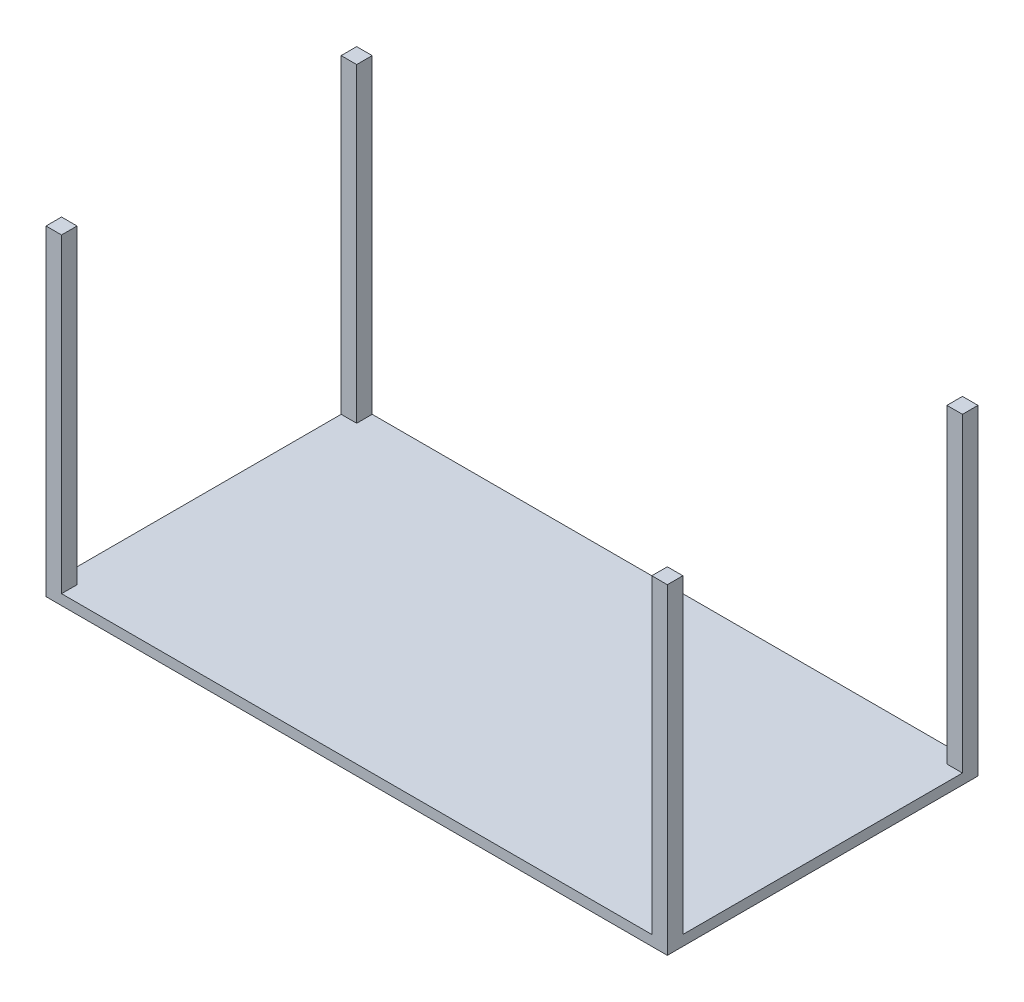
SolidWorks part; units mm, degrees
ref_plane "Front" through (0, 0, 0) normal (0, 0, 1) x (1, 0, 0)
ref_plane "Top" through (0, 0, 0) normal (0, 1, 0) x (1, 0, 0)
ref_plane "Right" through (0, 0, 0) normal (1, 0, 0) x (0, 0, -1)
sketch "Sketch1" plane through (0, 0, 0) normal (0, 1, 0) x (1, 0, 0)
  line L1 (-762, 381) -> (762, 381)
  line L2 (-762, 381) -> (-762, -381)
  line L3 (-762, -381) -> (762, -381)
  line L4 (762, 381) -> (762, -381)
  line L5 (-762, 381) -> (762, -381) construction
  line L6 (-762, -381) -> (762, 381) construction
  point P0 (0, 0)
  dimension "D1" = 1524
  dimension "D2" = 762
extrude "Boss-Extrude1" add sketch "Sketch1" along normal blind 25.4
sketch "Sketch2" plane through (0, 25.4, 0) normal (0, 1, 0) x (1, 0, 0)
  line L1 (-762, 381) -> (-723.9, 381)
  line L2 (-762, 381) -> (-762, 342.9)
  line L3 (-762, 342.9) -> (-723.9, 342.9)
  line L4 (-723.9, 381) -> (-723.9, 342.9)
  line L5 (-762, -381) -> (-723.9, -381)
  line L6 (-762, -381) -> (-762, -342.9)
  line L7 (-762, -342.9) -> (-723.9, -342.9)
  line L8 (-723.9, -381) -> (-723.9, -342.9)
  line L9 (762, 381) -> (723.9, 381)
  line L10 (762, 381) -> (762, 342.9)
  line L11 (762, 342.9) -> (723.9, 342.9)
  line L12 (723.9, 381) -> (723.9, 342.9)
  line L13 (762, -381) -> (723.9, -381)
  line L14 (762, -381) -> (762, -342.9)
  line L15 (762, -342.9) -> (723.9, -342.9)
  line L16 (723.9, -381) -> (723.9, -342.9)
  dimension "D1" = 38.1
extrude "Boss-Extrude2" add sketch "Sketch2" along normal blind 762
